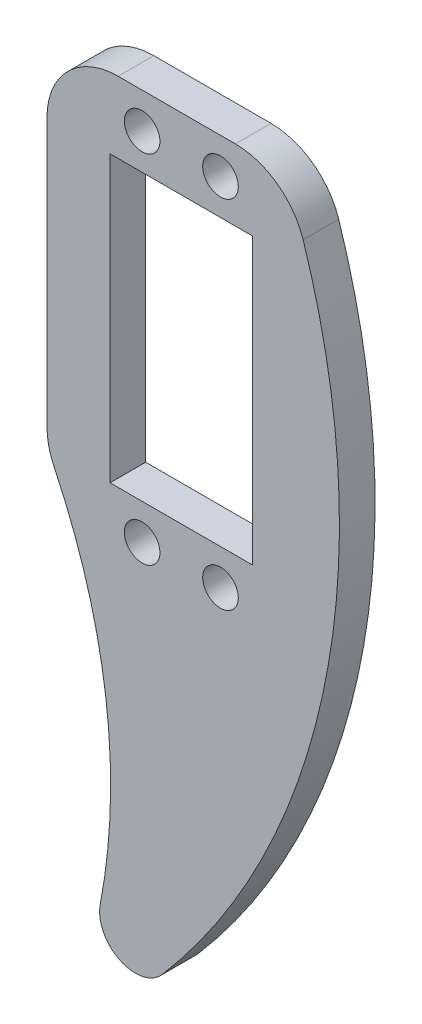
SolidWorks part; units mm, degrees
ref_plane "Plan de face" through (0, 0, 0) normal (0, 0, 1) x (1, 0, 0)
ref_plane "Plan de dessus" through (0, 0, 0) normal (0, 1, 0) x (1, 0, 0)
ref_plane "Plan de droite" through (0, 0, 0) normal (1, 0, 0) x (0, 0, -1)
sketch "Esquisse1" plane through (0, 0, 0) normal (0, 0, 1) x (1, 0, 0)
  line L0 (-8.8556, 10) -> (24.5698, 10)
  line L1 (0, 0) -> (20, 0)
  line L2 (0, 0) -> (0, -40)
  line L3 (0, -40) -> (20, -40)
  line L4 (20, 0) -> (20, -40)
  line L5 (-8.8556, 10) -> (-8.8556, -40)
  arc A0 (24.5698, 10) -> (7.3304, -96.1084) centre (-70.9451, -28.9363) cw
  arc A1 (-1.3733, -91.9042) -> (-8.8556, -40) centre (-79.9222, -76.7362) ccw
  arc A2 (-1.3733, -91.9042) -> (7.3304, -96.1084) centre (3.536, -92.8522) ccw
  point P13 (-7.1656, -110)
  dimension "D5" = 80
  dimension "D6" = 5
  dimension "D1" = 20
  dimension "D2" = 40
  dimension "D3" = 10
  dimension "D4" = 120
extrude "Boss.-Extru.1" add sketch "Esquisse1" along normal blind 5
fillet "Congé1" radius 10 1 edges at (24.5698, 10, 2.5)
fillet "Congé2" radius 10 2 edges at (-8.8556, -40, 2.5) (-8.8556, 10, 2.5)
sketch "Esquisse2" plane through (0, 0, 5) normal (0, 0, 1) x (1, 0, 0)
  line L0 (20, 0) -> (0, 0) construction
  line L1 (0, 0) -> (0, -40) construction
  line L2 (20, -40) -> (20, 0) construction
  line L3 (0, -40) -> (20, -40) construction
  circle A0 centre (4.5, 5) radius 2.5
  circle A1 centre (15.5, 5) radius 2.5
  circle A2 centre (4.5, -45) radius 2.5
  circle A3 centre (15.5, -45) radius 2.5
  dimension "D3" = 5
  dimension "D4" = 5
  dimension "D7" = 5
  dimension "D11" = 5
  dimension "D1" = 5
  dimension "D2" = 5
  dimension "D5" = 4.5
  dimension "D6" = 4.5
  dimension "D8" = 5
  dimension "D9" = 5
  dimension "D10" = 4.5
extrude "Enlèv. mat.-Extru.1" cut sketch "Esquisse2" against normal blind 10
